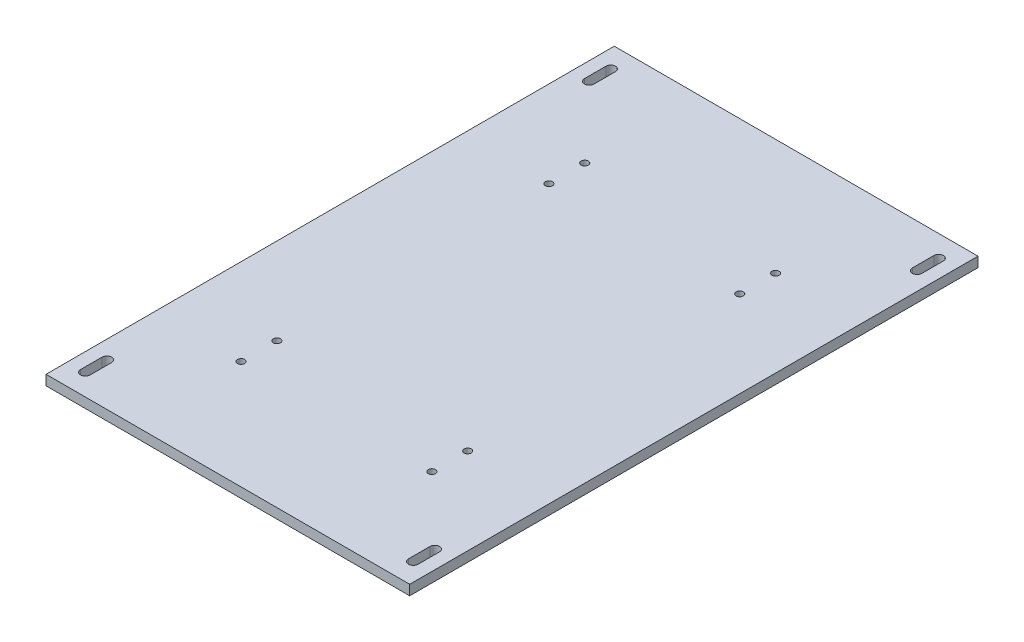
SolidWorks part; units mm, degrees
ref_plane "Front Plane" through (0, 0, 0) normal (0, 0, 1) x (1, 0, 0)
ref_plane "Top Plane" through (0, 0, 0) normal (0, 1, 0) x (1, 0, 0)
ref_plane "Right Plane" through (0, 0, 0) normal (1, 0, 0) x (0, 0, -1)
sketch "Sketch1" plane through (0, 0, 0) normal (0, 1, 0) x (1, 0, 0)
  line L1 (-101.6, -158.75) -> (101.6, -158.75)
  line L2 (-101.6, -158.75) -> (-101.6, 158.75)
  line L3 (-101.6, 158.75) -> (101.6, 158.75)
  line L4 (101.6, -158.75) -> (101.6, 158.75)
  line L5 (-101.6, -158.75) -> (101.6, 158.75) construction
  line L6 (-101.6, 158.75) -> (101.6, -158.75) construction
  point P0 (0, 0)
  dimension "D1" = 203.2
  dimension "D2" = 317.5
extrude "Boss-Extrude1" add sketch "Sketch1" along normal blind 5.588
extrude "Cut-Extrude2" cut sketch "Sketch3" against normal through all
sketch "Sketch3" plane through (-338.2608, 0, 0) normal (0, -1, 0) x (1, 0, 0)
  circle A8 centre (391.5608, -93.9361) radius 2
  circle A9 centre (391.5608, -73.9361) radius 2
  circle A10 centre (391.5608, 78.0639) radius 2
  circle A11 centre (391.5608, 98.0639) radius 2
mirror "Mirror2" about plane through (0, 0, 0) normal (1, 0, 0) of "Cut-Extrude2"
sketch "Sketch4" plane through (0, 0, -158.75) normal (0, 0, -1) x (-1, 0, 0)
  line L4 (-101.6, 0) -> (101.6, 0)
  line L5 (101.6, 0) -> (101.6, 5.588)
  line L6 (101.6, 5.588) -> (-101.6, 5.588)
  line L7 (-101.6, 5.588) -> (-101.6, 0)
  line L8 (-101.6, 0) -> (101.6, 0)
  line L9 (101.6, 0) -> (101.6, 5.588)
  line L10 (101.6, 5.588) -> (-101.6, 5.588)
  line L11 (-101.6, 5.588) -> (-101.6, 0)
  dimension "D1" = 0
extrude "Boss-Extrude2" [suppressed] add sketch "Sketch4" along normal blind 127
extrude "Cut-Extrude4" cut sketch "Sketch6" against normal through all
sketch "Sketch6" plane through (-338.2608, 5.588, 0) normal (0, 1, 0) x (1, 0, 0)
  circle A1 centre (429.8608, 136.812) radius 2.65
sketch "Sketch7" plane through (0, 0, 0) normal (0, -1, 0) x (1, 0, 0)
  line L0 (91.6, -136.812) -> (91.6, -146.75) construction
  line L1 (91.6, -146.75) -> (91.6, -134.75) construction
  line L2 (88.95, -146.75) -> (88.95, -134.75)
  line L3 (94.25, -146.75) -> (94.25, -134.75)
  line L4 (101.6, -158.75) -> (-101.6, -158.75) construction
  arc A0 (88.95, -146.75) -> (94.25, -146.75) centre (91.6, -146.75) ccw
  arc A1 (94.25, -134.75) -> (88.95, -134.75) centre (91.6, -134.75) ccw
  circle A2 centre (91.6, -136.812) radius 2.65 construction
  point P4 (91.6, -140.75)
  dimension "D1" = 12
  dimension "D2" = 12
extrude "Cut-Extrude5" cut sketch "Sketch7" against normal through all
mirror "Mirror3" about plane through (0, 0, 0) normal (1, 0, 0) of "Cut-Extrude5" second plane through (0, 0, 0) second plane normal (0, 0, 1)
